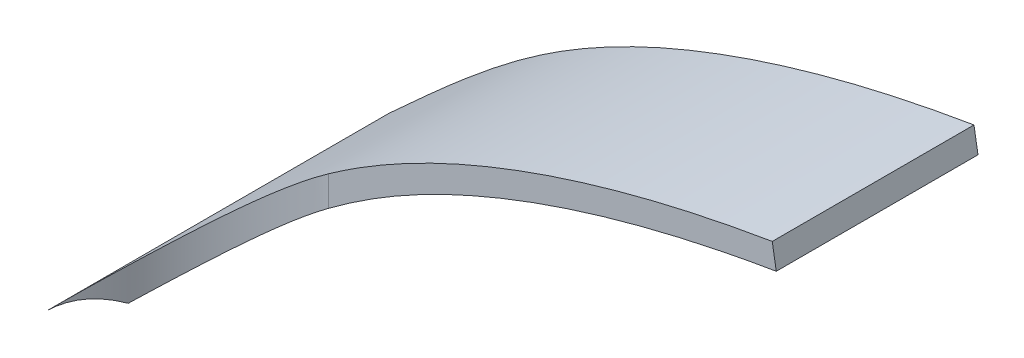
SolidWorks part; units mm, degrees
ref_plane "前视基准面" through (0, 0, 0) normal (0, 0, 1) x (1, 0, 0)
ref_plane "上视基准面" through (0, 0, 0) normal (0, 1, 0) x (1, 0, 0)
ref_plane "右视基准面" through (0, 0, 0) normal (1, 0, 0) x (0, 0, -1)
sketch "草图1" plane through (0, 0, 0) normal (0, 0, 1) x (1, 0, 0)
  line L0 (-29.364, 0) -> (29.364, 0) construction
  line L1 (0, 26.3958) -> (0, -25.1943) construction
  line L2 (-20.4594, 17) -> (13.1095, 17) construction
  line L3 (-20.9541, 10) -> (15.4417, 10) construction
  line L4 (-14.5, 22.6502) -> (-14.5, -16.5724) construction
  line L5 (-14.5, 10) -> (0, 17) construction
  line L6 (0.0993, 16.4083) -> (0, 17)
  line L7 (-14.5, 10) -> (-14.0953, 9.557)
  spline S0 degree 3 poles (-14.5, 10) (-13.2757, 11.1183) (-10.6672, 13.5203) (-5.6205, 15.8092) (-1.9239, 16.6772) (0, 17) knots 0 0 0 0 0.304838 0.643087 1 1 1 1
  spline S1 degree 1 poles (-14.0953, 9.557) (0.0993, 16.4083) knots 0 0 1 1 construction
  spline S2 degree 3 poles (-14.0953, 9.557) (-13.1018, 10.4645) (-11.5913, 11.8562) (-9.4082, 13.3081) (-7.0317, 14.5122) (-3.8568, 15.62) (-1.2248, 16.1861) (0.0993, 16.4083) knots 0 0 0 0 0.25 0.375 0.5 0.75 1 1 1 1
  dimension "D1" = 10
  dimension "D2" = 17
  dimension "D3" = 14.5
  dimension "D4" = 0.6
  dimension "D5" = 0.6
  dimension "D6" = 1.2
  dimension "D7" = 1.2
  dimension "D8" = 0.6
extrude "凸台-拉伸1" add sketch "草图1" along normal blind 10
sketch "草图2" plane through (0, 0, 0) normal (0, 1, 0) x (1, 0, 0)
  line L0 (6.3953, 0) -> (-19.5328, 0) construction
  line L1 (0, 7.2061) -> (0, -15.5323) construction
  line L2 (2.5424, -5) -> (-11, -5)
  line L3 (-14.5, -10) -> (0, -10) construction
  line L4 (-14.5, -10) -> (-14.5, -8.5)
  line L5 (-14.5, -10) -> (-14.5, 0) construction
  line L6 (2.5424, -5) -> (2.5424, -12.2709)
  line L7 (2.5424, -12.2709) -> (-14.5, -12.2709)
  line L8 (-14.5, -12.2709) -> (-14.5, -10)
  arc A0 (-14.5, -8.5) -> (-11, -5) centre (-11, -8.5) cw
  dimension "D2" = 3.5
  dimension "D1" = 5
extrude "切除-拉伸1" cut sketch "草图2" along normal blind 31
